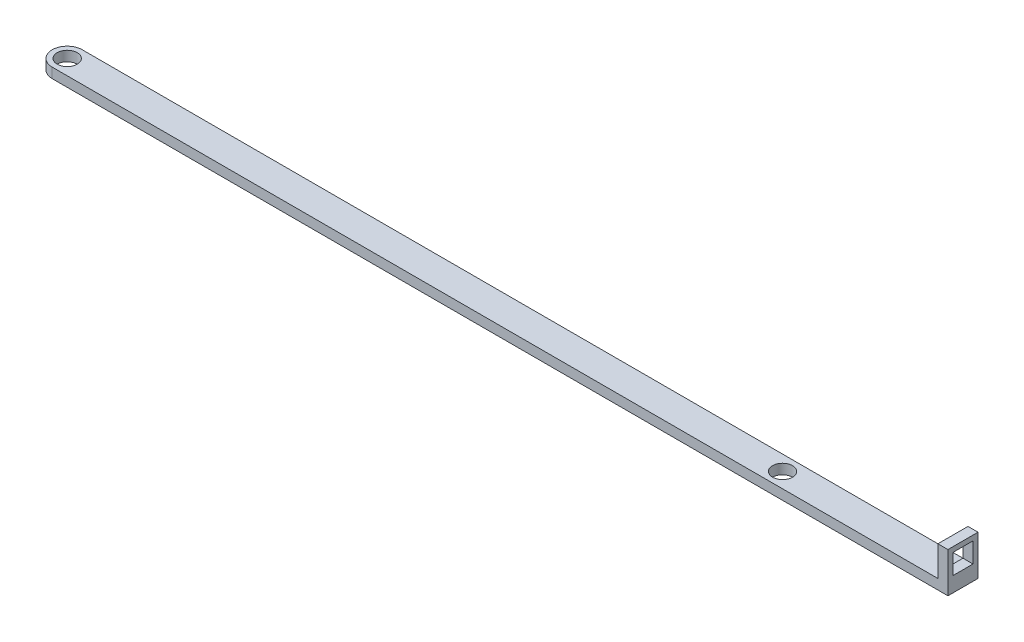
SolidWorks part; units mm, degrees
ref_plane "Front" through (0, 0, 0) normal (0, 0, 1) x (1, 0, 0)
ref_plane "Top" through (0, 0, 0) normal (0, 1, 0) x (1, 0, 0)
ref_plane "Right" through (0, 0, 0) normal (1, 0, 0) x (0, 0, -1)
sketch "Sketch1" plane through (0, 0, 0) normal (0, 1, 0) x (1, 0, 0)
  line L0 (0, 0) -> (-567.5074, 0) construction
  line L1 (0, -9.525) -> (-567.5074, -9.525)
  line L2 (0, 9.525) -> (-567.5074, 9.525)
  arc A0 (0, -9.525) -> (0, 9.525) centre (0, 0) ccw
  arc A1 (-567.5074, 9.525) -> (-567.5074, -9.525) centre (-567.5074, 0) ccw
  circle A2 centre (-567.5074, 0) radius 6.35
  point P3 (-283.7537, 0)
  dimension "D1" = 9.525
  dimension "D2" = 12.7
  dimension "D3" = 567.5074
extrude "Boss-Extrude1" add sketch "Sketch1" along normal blind 6.35
sketch "Sketch2" plane through (0, 6.35, 0) normal (0, 1, 0) x (1, 0, 0)
  line L0 (-114.3, 9.525) -> (-114.3, -9.525) construction
  line L1 (0, 9.525) -> (-567.5074, 9.525) construction
  line L2 (-567.5074, -9.525) -> (0, -9.525) construction
  circle A0 centre (-114.3, 0) radius 6.35
  circle A1 centre (-567.5074, 0) radius 6.35 construction
  point P2 (-567.5074, 0)
  point P3 (-114.3, 0)
  dimension "D1" = 12.7
  dimension "D2" = 453.2074
extrude "Cut-Extrude1" cut sketch "Sketch2" against normal blind 6.35
sketch "Sketch3" plane through (0, 6.35, 0) normal (0, 1, 0) x (1, 0, 0)
  line L0 (0, -9.525) -> (0, 9.525)
  arc A0 (0, -9.525) -> (0, 9.525) centre (0, 0) ccw construction
  arc A1 (0, 9.525) -> (0, -9.525) centre (0, 0) cw
extrude "Cut-Extrude2" cut sketch "Sketch3" against normal blind 6.35
sketch "Sketch4" plane through (0, 6.35, 0) normal (0, 1, 0) x (1, 0, 0)
  line L0 (-567.5074, -9.525) -> (0, -9.525) construction
  line L1 (0, 9.525) -> (-6.35, 9.525)
  line L2 (0, 9.525) -> (0, -9.525)
  line L3 (0, -9.525) -> (-6.35, -9.525)
  line L4 (-6.35, 9.525) -> (-6.35, -9.525)
  dimension "D1" = 6.35
extrude "Boss-Extrude2" add sketch "Sketch4" along normal blind 19.05
sketch "Sketch5" plane through (0, 0, 0) normal (1, 0, 0) x (0, 0, -1)
  line L0 (0, 25.4) -> (0, 22.225) construction
  line L1 (-6.35, 22.225) -> (6.35, 22.225)
  line L2 (-6.35, 22.225) -> (-6.35, 9.525)
  line L3 (-6.35, 9.525) -> (6.35, 9.525)
  line L4 (6.35, 22.225) -> (6.35, 9.525)
  line L7 (-9.525, 25.4) -> (9.525, 25.4) construction
  line L8 (-6.35, 15.875) -> (-9.525, 15.875) construction
  line L9 (-9.525, 25.4) -> (-9.525, 0) construction
  line L10 (6.35, 15.875) -> (9.525, 15.875) construction
  line L11 (9.525, 25.4) -> (9.525, 0) construction
  dimension "D1" = 12.7
extrude "Cut-Extrude3" cut sketch "Sketch5" against normal blind 19.05
